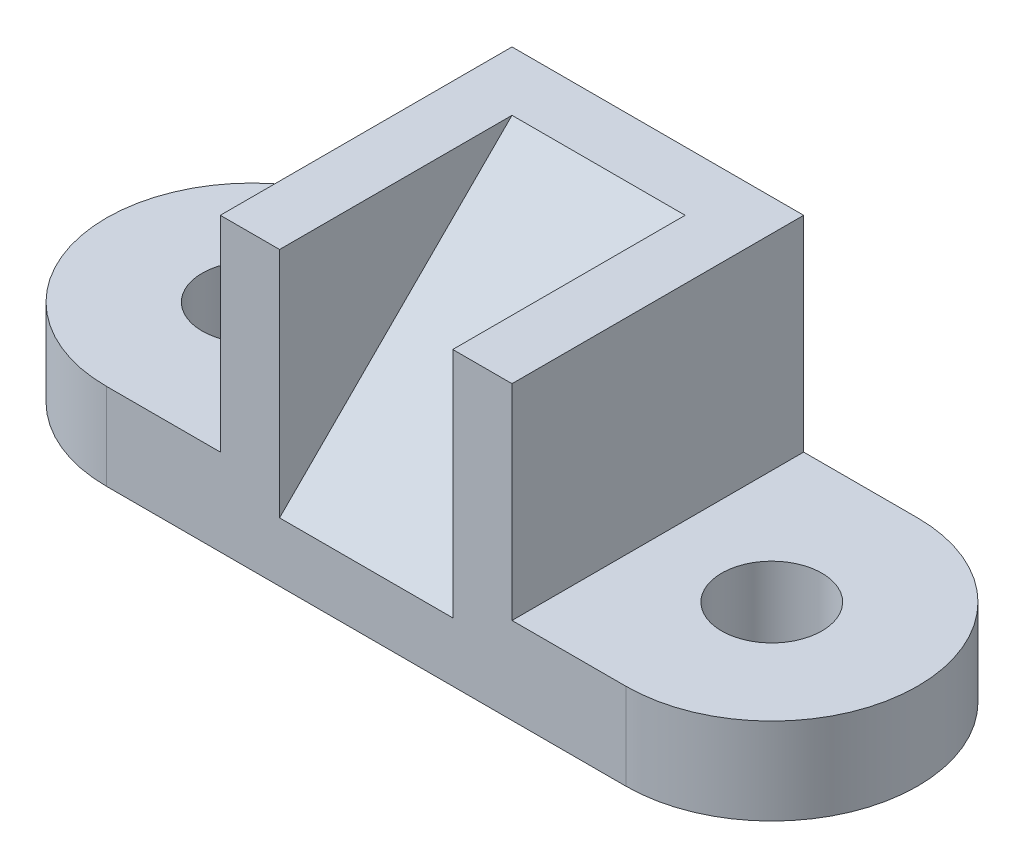
SolidWorks part; units mm, degrees
ref_plane "Front Plane" through (0, 0, 0) normal (0, 0, 1) x (1, 0, 0)
ref_plane "Top Plane" through (0, 0, 0) normal (0, 1, 0) x (1, 0, 0)
ref_plane "Right Plane" through (0, 0, 0) normal (1, 0, 0) x (0, 0, -1)
sketch "Sketch1" plane through (0, 0, 0) normal (0, 1, 0) x (1, 0, 0)
  line L0 (-57, 0) -> (57, 0) construction
  line L2 (-57, 32) -> (57, 32)
  line L3 (-57, -32) -> (57, -32)
  arc A0 (-57, 32) -> (-57, -32) centre (-57, 0) ccw
  arc A1 (57, -32) -> (57, 32) centre (57, 0) ccw
  circle A2 centre (-57, 0) radius 11
  circle A3 centre (57, 0) radius 11
  point P5 (0, 0)
  dimension "D2" = 32
  dimension "D3" = 22
  dimension "D4" = 22
  dimension "D1" = 114
extrude "Boss-Extrude1" add sketch "Sketch1" along normal blind 19
sketch "Sketch2" plane through (0, 19, 0) normal (0, 1, 0) x (1, 0, 0)
  line L1 (32, -32) -> (-32, -32)
  line L2 (32, -32) -> (32, 32)
  line L3 (32, 32) -> (-32, 32)
  line L4 (-32, -32) -> (-32, 32)
  line L5 (32, -32) -> (-32, 32) construction
  line L6 (32, 32) -> (-32, -32) construction
  point P0 (0, 0)
  dimension "D1" = 64
  dimension "D2" = 64
extrude "Boss-Extrude3" add sketch "Sketch2" along normal blind 45
sketch "Sketch4" plane through (0, 64, 0) normal (0, 1, 0) x (1, 0, 0)
  line L0 (32, 32) -> (-32, 32) construction
  line L1 (19, -32) -> (-19, -32)
  line L2 (19, -32) -> (19, 19)
  line L3 (19, 19) -> (-19, 19)
  line L4 (-19, -32) -> (-19, 19)
  line L7 (-32, 32) -> (-32, -32) construction
  line L8 (-32, -32) -> (32, -32) construction
  point P0 (0, 0)
  dimension "D1" = 13
  dimension "D2" = 13
  dimension "D3" = 38
extrude "Cut-Extrude1" cut sketch "Sketch4" against normal blind 51 and the other way through all
sketch "Sketch5" plane through (19, 0, 0) normal (-1, 0, 0) x (0, 0, 1)
  line L0 (-19, 64) -> (32, 13)
  line L3 (-19, 64) -> (-19, 13)
  line L4 (-19, 13) -> (32, 13)
  line L5 (32, 64) -> (32, 13) construction
extrude "Boss-Extrude4" add sketch "Sketch5" along normal up to next
